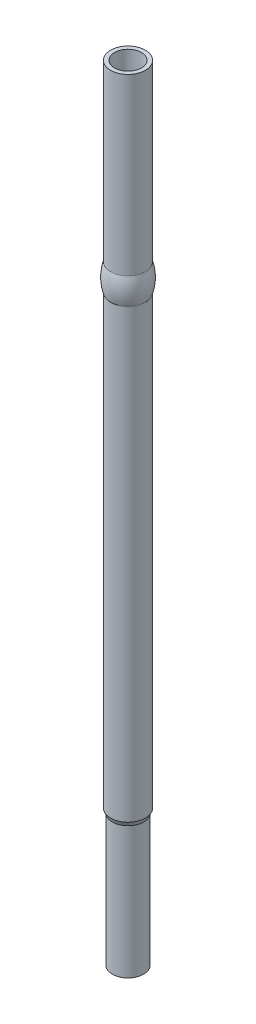
SolidWorks part; units mm, degrees
material "Nickel silver 65-12, UNS C75700"
ref_plane "Front" through (0, 0, 0) normal (0, 0, 1) x (1, 0, 0)
ref_plane "Top" through (0, 0, 0) normal (0, 1, 0) x (1, 0, 0)
ref_plane "Right" through (0, 0, 0) normal (1, 0, 0) x (0, 0, -1)
sketch "Sketch1" plane through (0, 0, 0) normal (1, 0, 0) x (0, 0, -1)
  line L0 (0.51, 0) -> (0.51, -18.54)
  line L1 (0.51, -18.54) -> (0, -18.54)
  line L2 (0, -18.54) -> (0, -24.72)
  line L3 (0, -24.72) -> (0.455, -24.72)
  line L4 (0.455, -24.72) -> (0.455, -29.72)
  line L5 (0.455, -29.72) -> (0.595, -29.72)
  line L6 (0.595, -29.72) -> (0.595, -24.72)
  line L7 (0.595, -24.72) -> (0.66, -24.56)
  line L8 (0.66, -24.56) -> (0.66, -7.62)
  line L9 (0.66, -7.62) -> (0.66, -6.62) construction
  line L10 (0.66, -6.62) -> (0.66, 0)
  line L11 (0.66, 0) -> (0.51, 0)
  arc A0 (0.66, -6.62) -> (0.66, -7.62) centre (-0.9692, -7.12) cw
  point P9 (0.6275, -24.64)
  point P11 (0.735, -7.12)
  dimension "D1" = 0.455
  dimension "D2" = 0.595
  dimension "D3" = 0.66
  dimension "D4" = 0.51
  dimension "D5" = 29.72
  dimension "D6" = 24.64
  dimension "D7" = 0.735
  dimension "D8" = 7.62
  dimension "D9" = 18.54
  dimension "D10" = 5
  dimension "D11" = 1
revolve "Revolve1" add sketch "Sketch1" angle 360 about L2
equation "\"D9@Sketch1\"=33.27-((38.10-29.72)+6.35)"
equation "\"D1@Sketch1\"=0.91/2"
equation "\"D2@Sketch1\"=1.19/2"
equation "\"D7@Sketch1\"=1.47/2"
equation "\"D3@Sketch1\"=1.32/2"
equation "\"D4@Sketch1\"=1.02/2"
